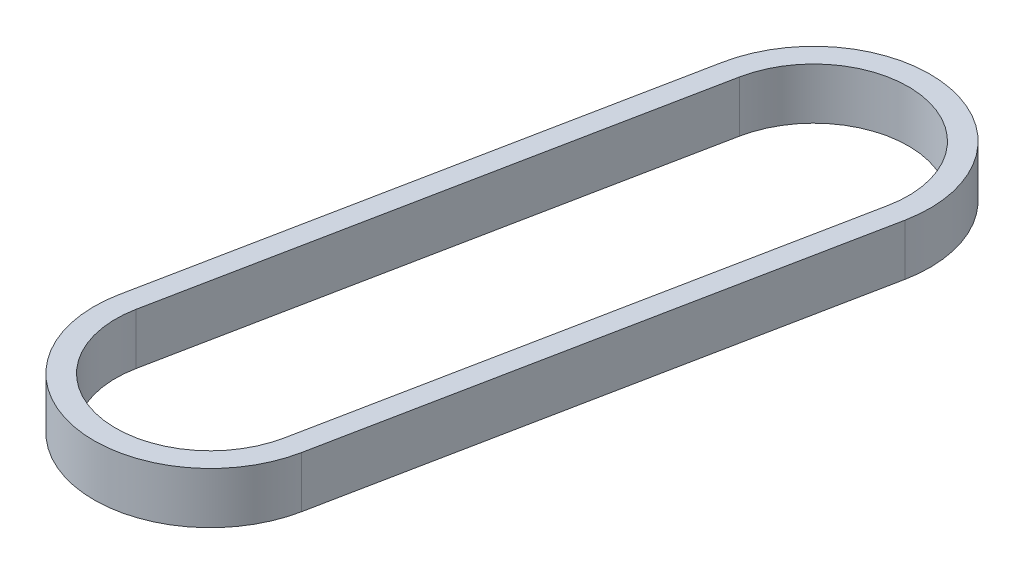
SolidWorks part; units mm, degrees
material "NEOPRENE"
ref_plane "Front Plane" through (0, 0, 0) normal (0, 0, 1) x (1, 0, 0)
ref_plane "Top Plane" through (0, 0, 0) normal (0, 1, 0) x (1, 0, 0)
ref_plane "Right Plane" through (0, 0, 0) normal (1, 0, 0) x (0, 0, -1)
ref_plane "Plane1" through (0, 254.3926, 0) normal (0, 1, 0) x (1, 0, 0)
sketch "Sketch1" plane through (0, 254.3926, 0) normal (0, 1, 0) x (1, 0, 0)
  line L0 (5.4796, -177.6974) -> (-12.1502, -265.9467) construction
  line L1 (23.6211, -181.3216) -> (5.9913, -269.5709) construction
  line L2 (-12.662, -174.0732) -> (-30.2917, -262.3225) construction
  line L3 (25.4843, -181.6938) -> (7.8545, -269.9431)
  line L4 (-14.5252, -173.701) -> (-32.1549, -261.9503)
  line L5 (21.7579, -180.9494) -> (4.1281, -269.1987)
  line L6 (-10.7988, -174.4454) -> (-28.4286, -262.6948)
  circle A0 centre (5.4796, -177.6974) radius 18.5 construction
  circle A1 centre (5.4796, -177.6974) radius 18.5 construction
  circle A2 centre (-12.1502, -265.9467) radius 18.5 construction
  circle A3 centre (-12.1502, -265.9467) radius 18.5 construction
  arc A4 (23.6211, -181.3216) -> (-12.662, -174.0732) centre (5.4796, -177.6974) ccw construction
  arc A5 (-30.2917, -262.3225) -> (5.9913, -269.5709) centre (-12.1502, -265.9467) ccw construction
  arc A6 (-32.1549, -261.9503) -> (7.8545, -269.9431) centre (-12.1502, -265.9467) ccw
  arc A7 (25.4843, -181.6938) -> (-14.5252, -173.701) centre (5.4796, -177.6974) ccw
  arc A8 (-28.4286, -262.6948) -> (4.1281, -269.1987) centre (-12.1502, -265.9467) ccw
  arc A9 (21.7579, -180.9494) -> (-10.7988, -174.4454) centre (5.4796, -177.6974) ccw
  point P6 (-3.3353, -221.8221)
  dimension "D1" = 1.9
  dimension "D2" = 1.9
extrude "Boss-Extrude1" add sketch "Sketch1" along normal mid plane 9 contours L3 A7 L4 A6 A9 L5 A8 L6
